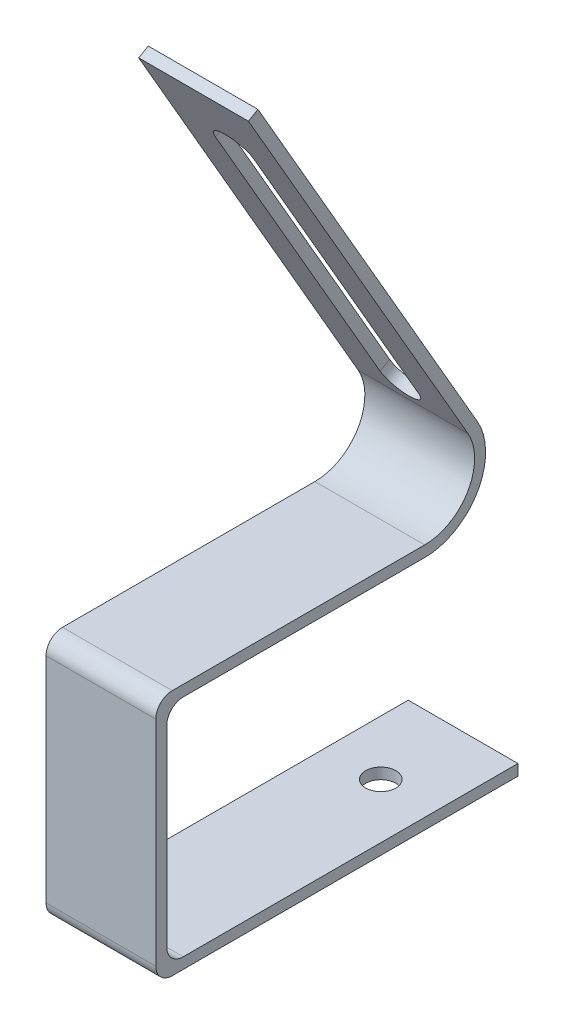
SolidWorks part; units mm, degrees
material "Liga de aço fundido"
ref_plane "Plano frontal" through (0, 0, 0) normal (0, 0, 1) x (1, 0, 0)
ref_plane "Plano superior" through (0, 0, 0) normal (0, 1, 0) x (1, 0, 0)
ref_plane "Plano direito" through (0, 0, 0) normal (1, 0, 0) x (0, 0, -1)
sketch "Esboço4" plane through (0, 0, 0) normal (1, 0, 0) x (0, 0, -1)
  line L0 (0, 0) -> (66, 0)
  line L1 (66, 0) -> (66, 2)
  line L2 (66, 2) -> (2, 2)
  line L3 (2, 2) -> (2, 43)
  line L4 (0, 0) -> (0, 45)
  line L5 (0, 45) -> (49, 45)
  line L6 (2, 43) -> (49, 43)
  line L7 (16.8821, 127.9342) -> (56.8821, 58.6522)
  line L8 (16.8821, 127.9342) -> (18.6142, 128.9342)
  line L9 (18.6142, 128.9342) -> (58.6142, 59.6522)
  arc A0 (56.8821, 58.6522) -> (49, 45) centre (49, 54.1015) cw
  arc A1 (58.6142, 59.6522) -> (49, 43) centre (49, 54.1015) cw
  dimension "D1" = 2
  dimension "D2" = 2
  dimension "D3" = 2
  dimension "D4" = 47
  dimension "D5" = 66
  dimension "D6" = 45
  dimension "D7" = 60
  dimension "D8" = 2
  dimension "D9" = 80
extrude "Ressalto-extrusão4" add sketch "Esboço4" along normal blind 20
fillet "Filete1" radius 3 4 edges at (10, 45, 0) (10, 0, 0) (10, 2, -2) (10, 43, -2)
sketch "Esboço5" plane through (0, 0, 0) normal (0, -1, 0) x (1, 0, 0)
  line L0 (20, -66) -> (0, -66) construction
  line L1 (20, -3) -> (20, -66) construction
  circle A0 centre (10, -51) radius 2.75
  dimension "D3" = 5.5
  dimension "D1" = 15
  dimension "D2" = 10
extrude "Corte-extrusão1" cut sketch "Esboço5" against normal up to surface (2 mm away) up to face at (10, 2, -35.5)
sketch "Esboço6" plane through (0, 40.2937, -69.7908) normal (0, 0.5, -0.866) x (-1, 0, 0)
  line L0 (-20, 102.3532) -> (0, 102.3532) construction
  line L2 (-13.5, 87.3532) -> (-13.5, 27.3532)
  line L4 (-6.5, 87.3532) -> (-6.5, 27.3532)
  arc A0 (-13.5, 87.3532) -> (-6.5, 87.3532) centre (-10, 87.3532) cw
  arc A1 (-13.5, 27.3532) -> (-6.5, 27.3532) centre (-10, 27.3532) ccw
  dimension "D1" = 15
  dimension "D2" = 7
  dimension "D3" = 60
extrude "Corte-extrusão2" cut sketch "Esboço6" against normal up to surface (2 mm away) up to face at (10, 93.2932, -36.8821)
